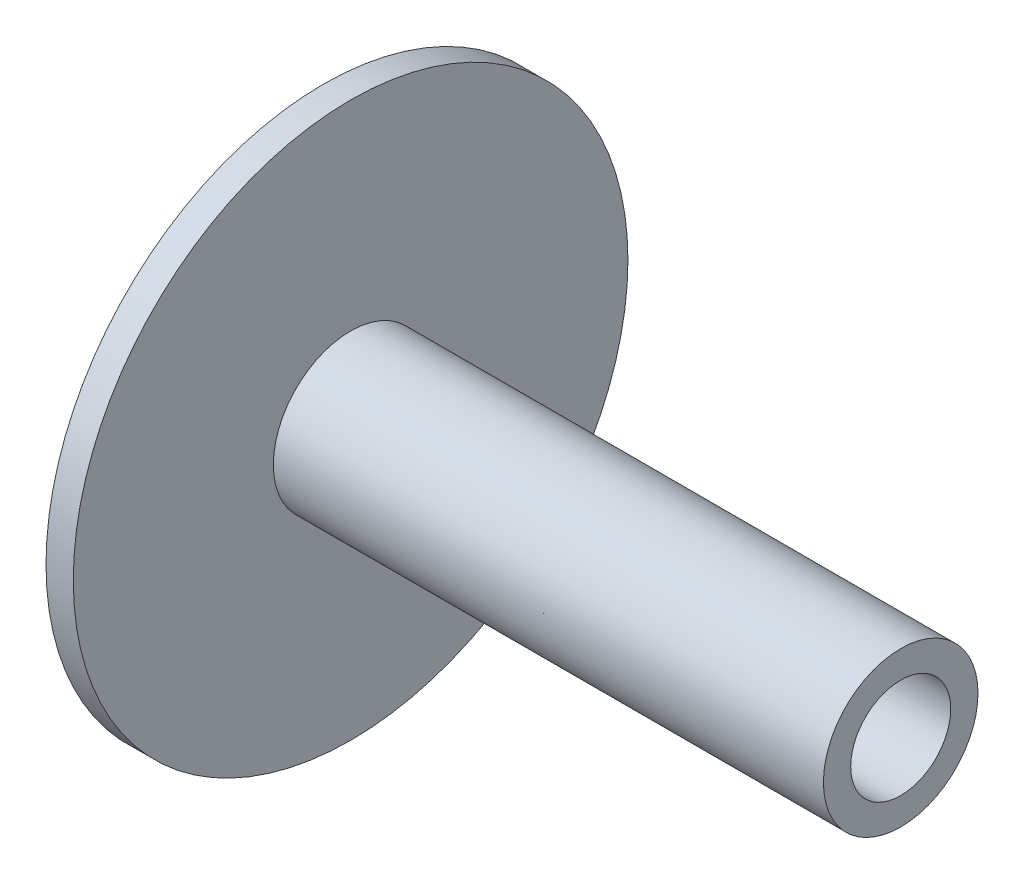
SolidWorks part; units mm, degrees
ref_plane "Front Plane" through (0, 0, 0) normal (0, 0, 1) x (1, 0, 0)
ref_plane "Top Plane" through (0, 0, 0) normal (0, 1, 0) x (1, 0, 0)
ref_plane "Right Plane" through (0, 0, 0) normal (1, 0, 0) x (0, 0, -1)
sketch "Sketch1" plane through (0, 0, 0) normal (1, 0, 0) x (0, 0, -1)
  circle A0 centre (0, 0) radius 2.2
  circle A1 centre (0, 0) radius 3.4
  dimension "D1" = 4.4
  dimension "D2" = 1.2
extrude "Boss-Extrude1" add sketch "Sketch1" along normal blind 24.2
sketch "Sketch2"
sketch "Sketch3" plane through (0, 0, 0) normal (-1, 0, 0) x (0, 0, 1)
  circle A1 centre (0, 0) radius 12.2
  circle A2 centre (0, 0) radius 2.2
  circle A3 centre (0, 0) radius 2.2
  dimension "D1" = 0
  dimension "D2" = 10
extrude "Boss-Extrude2" add sketch "Sketch3" along normal blind 1.2
